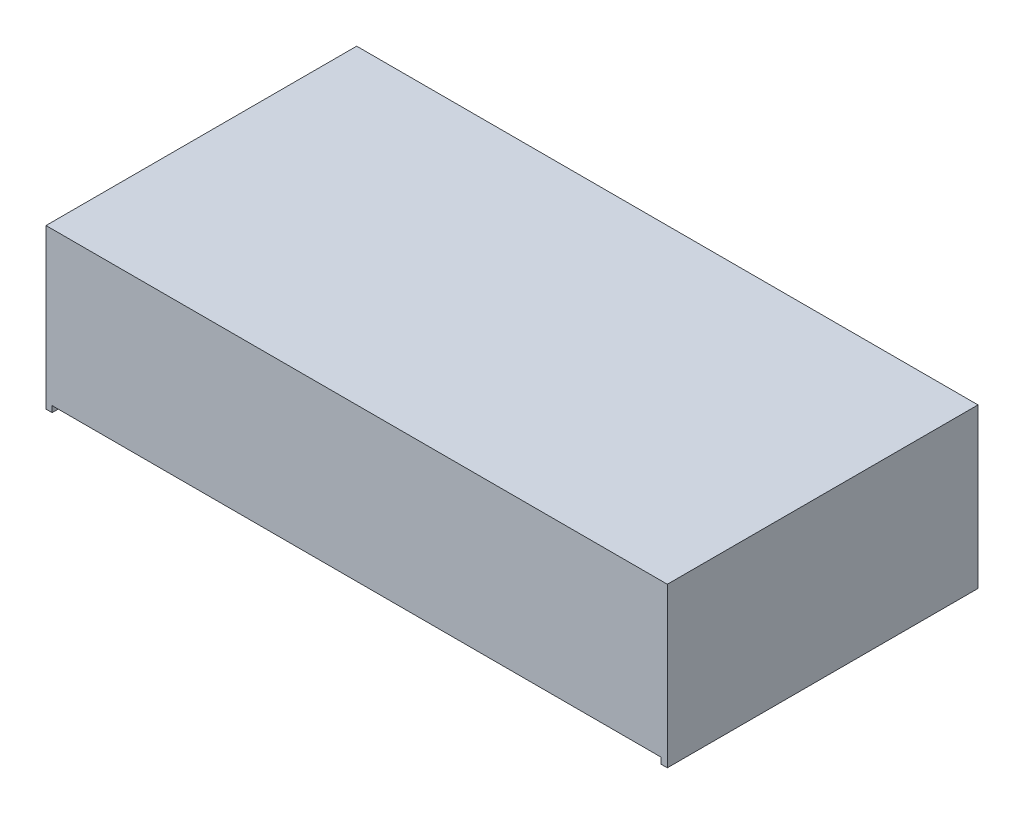
SolidWorks part; units mm, degrees
ref_plane "Front Plane" through (0, 0, 0) normal (0, 0, 1) x (1, 0, 0)
ref_plane "Top Plane" through (0, 0, 0) normal (0, 1, 0) x (1, 0, 0)
ref_plane "Right Plane" through (0, 0, 0) normal (1, 0, 0) x (0, 0, -1)
sketch "Sketch1" plane through (0, 0, 0) normal (0, 1, 0) x (1, 0, 0)
  line L1 (-25.4, 12.7) -> (25.4, 12.7)
  line L2 (-25.4, 12.7) -> (-25.4, -12.7)
  line L3 (-25.4, -12.7) -> (25.4, -12.7)
  line L4 (25.4, 12.7) -> (25.4, -12.7)
  line L5 (-25.4, 12.7) -> (25.4, -12.7) construction
  line L6 (-25.4, -12.7) -> (25.4, 12.7) construction
  point P0 (0, 0)
  dimension "D1" = 50.8
  dimension "D2" = 25.4
extrude "Boss-Extrude1" add sketch "Sketch1" along normal blind 13
sketch "Sketch2" plane through (0, 0, 12.7) normal (0, 0, 1) x (1, 0, 0)
  line L0 (-25.4, 13) -> (-25.4, 0) construction
  line L1 (-24.9, -2.0256) -> (24.9, -2.0256)
  line L2 (-24.9, -2.0256) -> (-24.9, 0.5)
  line L3 (-24.9, 0.5) -> (24.9, 0.5)
  line L4 (24.9, -2.0256) -> (24.9, 0.5)
  line L5 (25.4, 13) -> (25.4, 0) construction
  line L6 (-25.4, 0) -> (25.4, 0) construction
  dimension "D1" = 0.5
  dimension "D2" = 0.5
  dimension "D3" = 0.5
extrude "Cut-Extrude1" cut sketch "Sketch2" against normal up to next
